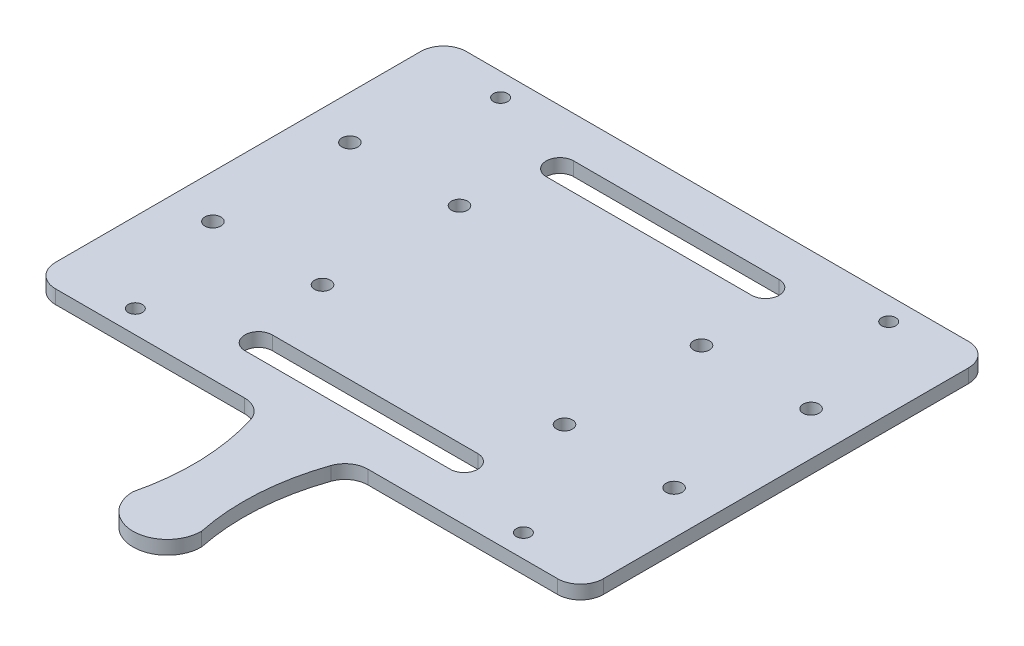
SolidWorks part; units mm, degrees
ref_plane "Front Plane" through (0, 0, 0) normal (0, 0, 1) x (1, 0, 0)
ref_plane "Top Plane" through (0, 0, 0) normal (0, 1, 0) x (1, 0, 0)
ref_plane "Right Plane" through (0, 0, 0) normal (1, 0, 0) x (0, 0, -1)
sketch "Sketch1" plane through (0, 0, 0) normal (0, 1, 0) x (1, 0, 0)
  line L1 (60, 45) -> (-60, 45)
  line L2 (60, 45) -> (60, -45)
  line L3 (60, -45) -> (-60, -45)
  line L4 (-60, 45) -> (-60, -45)
  point P8 (0, 45)
  point P9 (60, 0)
  dimension "D1" = 90
  dimension "D2" = 120
extrude "Boss-Extrude1" add sketch "Sketch1" along normal blind 3
fillet "圆角1" radius 5 4 edges at (60, 1.5, 45) (60, 1.5, -45) (-60, 1.5, 45) (-60, 1.5, -45)
sketch "草图1" plane through (0, 3, 0) normal (0, 1, 0) x (1, 0, 0)
  line L0 (-22.5, 33) -> (22.5, 33) construction
  line L1 (-22.5, 36) -> (22.5, 36)
  line L2 (-22.5, 30) -> (22.5, 30)
  line L3 (-22.5, -33) -> (22.5, -33) construction
  line L4 (-22.5, -30) -> (22.5, -30)
  line L5 (-22.5, -36) -> (22.5, -36)
  arc A0 (-22.5, 36) -> (-22.5, 30) centre (-22.5, 33) ccw
  arc A1 (22.5, 30) -> (22.5, 36) centre (22.5, 33) ccw
  arc A2 (-22.5, -30) -> (-22.5, -36) centre (-22.5, -33) ccw
  arc A3 (22.5, -36) -> (22.5, -30) centre (22.5, -33) ccw
  point P2 (0, 33)
  point P7 (0, -33)
  dimension "D1" = 33
  dimension "D2" = 33
  dimension "D3" = 6
  dimension "D4" = 6
  dimension "D5" = 45
  dimension "D6" = 45
extrude "切除-拉伸1" cut sketch "草图1" against normal through all
sketch "草图2" plane through (0, 3, 0) normal (0, 1, 0) x (1, 0, 0)
  line L0 (-55, -45) -> (55, -45) construction
  line L1 (-10, -45) -> (10, -45)
  line L2 (-8, -75) -> (7, -75) construction
  arc A0 (-10, -45) -> (-8, -75) centre (-56.5809, -63.1721) cw
  arc A1 (10, -45) -> (7, -75) centre (55.9368, -64.7437) ccw
  arc A2 (-8, -75) -> (7, -75) centre (-0.5, -75) ccw
  point P9 (0, -45)
  dimension "D1" = 30
  dimension "D2" = 50
  dimension "D3" = 50
  dimension "D4" = 20
  dimension "D5" = 15
  dimension "D6" = 8
extrude "凸台-拉伸1" add sketch "草图2" against normal up to surface (3 mm away) up to face at (0, 0, -33)
sketch "草图3" plane through (0, 3, 0) normal (0, 1, 0) x (1, 0, 0)
  circle A0 centre (42.5, -40) radius 1.55 construction
  circle A1 centre (42.5, 40) radius 1.55 construction
  circle A2 centre (-42.5, -40) radius 1.55 construction
  circle A3 centre (-42.5, 40) radius 1.55 construction
  circle A4 centre (42.5, -40) radius 1.55
  circle A5 centre (42.5, 40) radius 1.55
  circle A6 centre (-42.5, -40) radius 1.55
  circle A21 centre (-42.5, 40) radius 1.55
  circle A22 centre (-50.5, -15) radius 1.75 construction
  circle A23 centre (-26.5, -15) radius 1.75 construction
  circle A24 centre (-26.5, 15) radius 1.75 construction
  circle A25 centre (-50.5, 15) radius 1.75 construction
  circle A26 centre (-50.5, -15) radius 1.75
  circle A27 centre (-26.5, -15) radius 1.75
  circle A28 centre (-26.5, 15) radius 1.75
  circle A29 centre (-50.5, 15) radius 1.75
  circle A30 centre (50.5, -15) radius 1.75 construction
  circle A31 centre (50.5, 15) radius 1.75 construction
  circle A32 centre (26.5, -15) radius 1.75 construction
  circle A33 centre (26.5, 15) radius 1.75 construction
  circle A34 centre (50.5, -15) radius 1.75
  circle A35 centre (50.5, 15) radius 1.75
  circle A36 centre (26.5, -15) radius 1.75
  circle A37 centre (26.5, 15) radius 1.75
extrude "切除-拉伸2" cut sketch "草图3" against normal through all
fillet "圆角2" radius 5 2 edges at (10, 1.5, 45) (-10, 1.5, 45)
